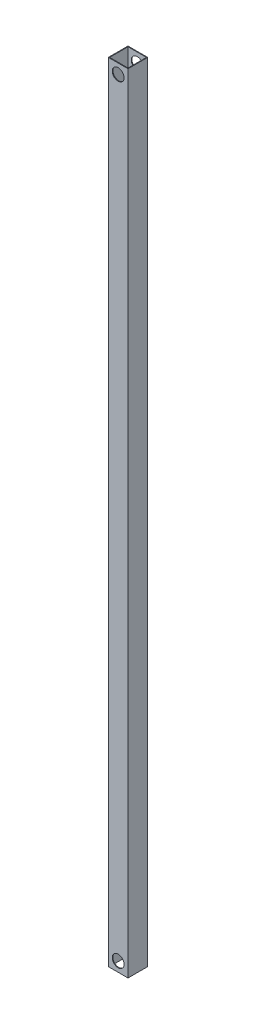
SolidWorks part; units mm, degrees
ref_plane "Alzado" through (0, 0, 0) normal (0, 0, 1) x (1, 0, 0)
ref_plane "Planta" through (0, 0, 0) normal (0, 1, 0) x (1, 0, 0)
ref_plane "Vista lateral" through (0, 0, 0) normal (1, 0, 0) x (0, 0, -1)
sketch "Croquis1" plane through (0, 0, 0) normal (0, 1, 0) x (1, 0, 0)
  line L1 (-5, 5) -> (5, 5)
  line L2 (-5, 5) -> (-5, -5)
  line L3 (-5, -5) -> (5, -5)
  line L4 (5, 5) -> (5, -5)
  line L5 (-5, 5) -> (5, -5) construction
  line L6 (-5, -5) -> (5, 5) construction
  point P0 (0, 0)
  dimension "D1" = 10
  dimension "D2" = 10
extrude "Saliente-Extruir1" add sketch "Croquis1" along normal blind 400
sketch "Croquis2" plane through (0, 400, 0) normal (0, 1, 0) x (1, 0, 0)
  line L0 (-5, 5) -> (-5, -5) construction
  line L1 (-4.683, 4.683) -> (4.683, 4.683)
  line L2 (-4.683, 4.683) -> (-4.683, -4.683)
  line L3 (-4.683, -4.683) -> (4.683, -4.683)
  line L4 (4.683, 4.683) -> (4.683, -4.683)
  line L5 (-4.683, 4.683) -> (4.683, -4.683) construction
  line L6 (-4.683, -4.683) -> (4.683, 4.683) construction
  line L7 (5, 5) -> (-5, 5) construction
  point P0 (0, 0)
  dimension "D1" = 0.317
  dimension "D2" = 0.317
extrude "Cortar-Extruir1" cut sketch "Croquis2" against normal blind 500
sketch "Croquis3" plane through (0, 0, 5) normal (0, 0, 1) x (1, 0, 0)
  line L0 (-5, 10) -> (5, 10) construction
  line L1 (-5, 400) -> (-5, 0) construction
  line L2 (5, 400) -> (5, 0) construction
  line L3 (-5, 0) -> (5, 0) construction
  line L4 (0, 0) -> (0, 10) construction
  line L5 (-5, 5) -> (5, 5) construction
  circle A0 centre (0, 5) radius 3
  dimension "D3" = 6
  dimension "D1" = 10
  dimension "D2" = 5
extrude "Cortar-Extruir2" cut sketch "Croquis3" against normal blind 500
sketch "Croquis4" plane through (0, 0, 5) normal (0, 0, 1) x (1, 0, 0)
  line L0 (5, 390) -> (-5, 390) construction
  line L1 (5, 400) -> (5, 0) construction
  line L2 (-5, 400) -> (-5, 0) construction
  line L3 (5, 395) -> (-5, 395) construction
  line L4 (5, 400) -> (-5, 400) construction
  line L5 (0, 400) -> (0, 390) construction
  circle A0 centre (0, 395) radius 3
  dimension "D3" = 6
  dimension "D1" = 10
  dimension "D2" = 5
extrude "Cortar-Extruir3" cut sketch "Croquis4" against normal blind 500
